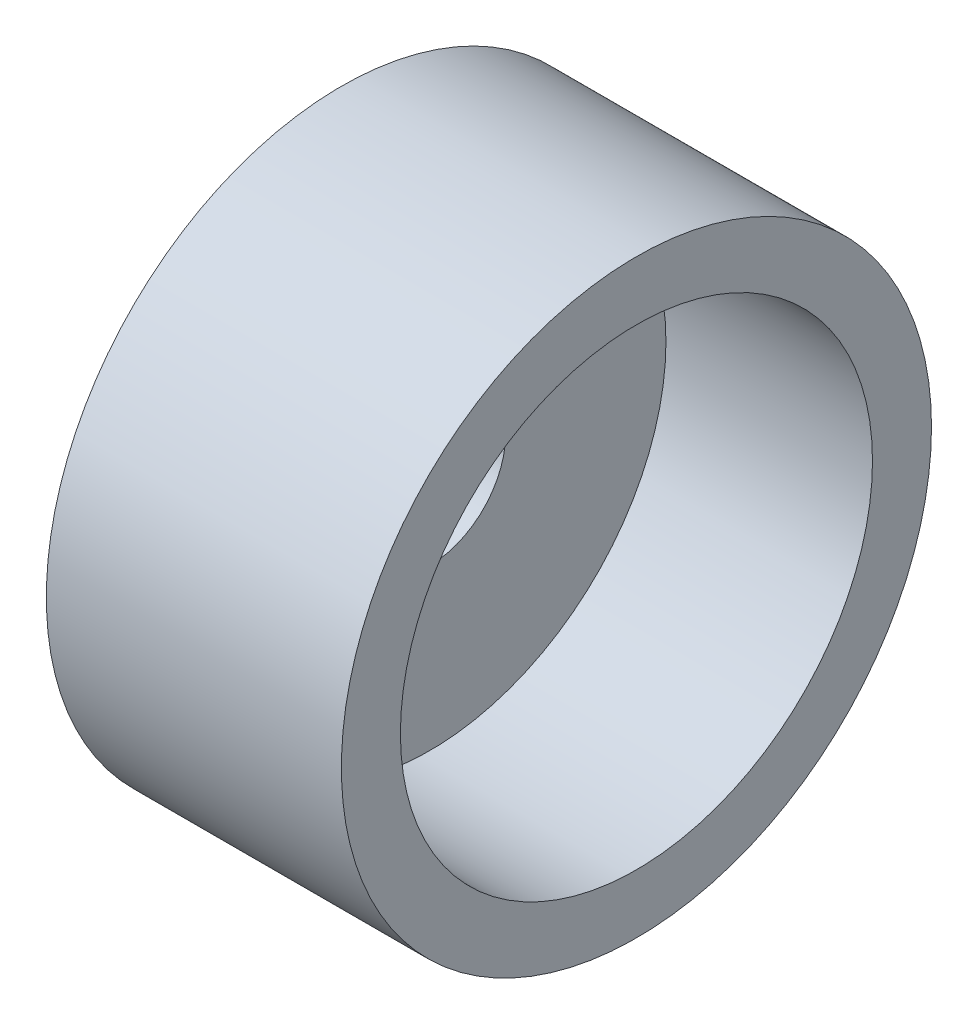
SolidWorks part; units mm, degrees
ref_plane "Plano frontal" through (0, 0, 0) normal (0, 0, 1) x (1, 0, 0)
ref_plane "Plano superior" through (0, 0, 0) normal (0, 1, 0) x (1, 0, 0)
ref_plane "Plano direito" through (0, 0, 0) normal (1, 0, 0) x (0, 0, -1)
sketch "Esboço1" plane through (0, 0, 0) normal (1, 0, 0) x (0, 0, -1)
  circle A0 centre (0, 0) radius 50
  dimension "D1" = 100
extrude "Ressalto-extrusão1" add sketch "Esboço1" along normal blind 50
sketch "Esboço2" plane through (50, 0, 0) normal (1, 0, 0) x (0, 0, -1)
  circle A0 centre (0, 0) radius 40
  circle A1 centre (0, 0) radius 50 construction
  dimension "D1" = 10
extrude "Corte-extrusão1" cut sketch "Esboço2" against normal offset from surface (35 mm away) 15 up to face at (0, 0, -50)
sketch "Esboço3" plane through (0, 0, 0) normal (-1, 0, 0) x (0, 0, 1)
  line L0 (-11.8125, 20.4598) -> (11.8125, 20.4598)
  line L1 (11.8125, 20.4598) -> (23.6249, 0)
  line L2 (23.6249, 0) -> (11.8125, -20.4598)
  line L3 (11.8125, -20.4598) -> (-11.8125, -20.4598)
  line L4 (-11.8125, -20.4598) -> (-23.6249, 0)
  line L5 (-23.6249, 0) -> (-11.8125, 20.4598)
  line L6 (0, -10.0082) -> (0, 30.7636) construction
  line L7 (0, 0) -> (23.6249, 0) construction
  line L8 (0, 0) -> (11.8125, 20.4598) construction
extrude "Corte-extrusão2" cut sketch "Esboço3" against normal blind 10
sketch "Esboço4" plane through (10, 0, 0) normal (-1, 0, 0) x (0, 0, 1)
  circle A0 centre (0, 0) radius 12.8327
extrude "Corte-extrusão3" cut sketch "Esboço4" against normal through all
